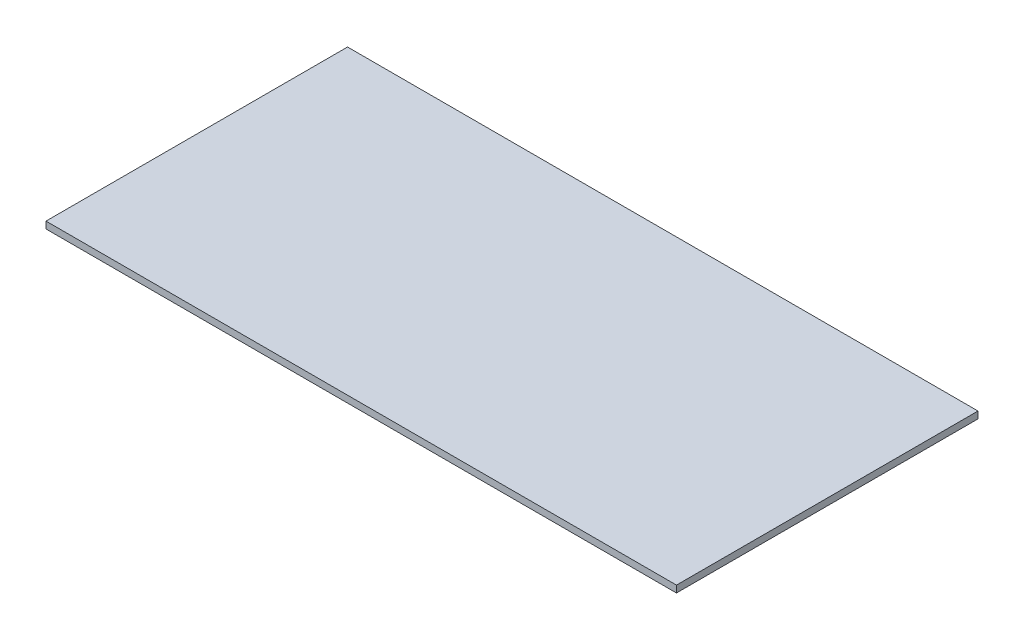
SolidWorks part; units mm, degrees
material "Acrylic (Medium-high impact)"
ref_plane "Front Plane" through (0, 0, 0) normal (0, 0, 1) x (1, 0, 0)
ref_plane "Top Plane" through (0, 0, 0) normal (0, 1, 0) x (1, 0, 0)
ref_plane "Right Plane" through (0, 0, 0) normal (1, 0, 0) x (0, 0, -1)
sketch "Sketch1" plane through (0, 0, 0) normal (0, 1, 0) x (1, 0, 0)
  line L1 (-292.1, 139.7) -> (292.1, 139.7)
  line L2 (-292.1, 139.7) -> (-292.1, -139.7)
  line L3 (-292.1, -139.7) -> (292.1, -139.7)
  line L4 (292.1, 139.7) -> (292.1, -139.7)
  line L5 (-292.1, 139.7) -> (292.1, -139.7) construction
  line L6 (-292.1, -139.7) -> (292.1, 139.7) construction
  point P4 (0, 0)
  dimension "D1" = 279.4
  dimension "D2" = 584.2
extrude "Baseplate" add sketch "Sketch1" along normal blind 6.35
sketch "Mounting Points" plane through (0, 6.35, 0) normal (0, 1, 0) x (1, 0, 0)
  line L0 (-292.1, -127) -> (292.1, -127) construction
  line L1 (-292.1, 139.7) -> (-292.1, -139.7) construction
  line L2 (292.1, -139.7) -> (292.1, 139.7) construction
  line L3 (-292.1, -139.7) -> (292.1, -139.7) construction
  line L4 (-55, 0) -> (55, 0) construction
  line L5 (-292.1, 127) -> (292.1, 127) construction
  point P8 (133.35, -127)
  point P9 (-240.5126, -127)
  point P10 (-19.05, -127)
  point P11 (-69.85, -127)
  point P20 (-69.85, 127)
  point P21 (-19.05, 127)
  point P22 (-240.5126, 127)
  point P23 (133.35, 127)
  dimension "D1" = 12.7
  dimension "D2" = 158.75
  dimension "D3" = 50.8
  dimension "D4" = 152.4
  dimension "D5" = 170.6626
sketch "Battery Adaptors" plane through (0, 6.35, 0) normal (0, 1, 0) x (1, 0, 0)
  line L0 (208.4146, -118.6932) -> (290.6217, -118.6932) construction
  line L1 (208.4146, -118.6932) -> (208.4146, -20.2682) construction
  line L2 (208.4146, -20.2682) -> (290.6217, -20.2682) construction
  line L3 (290.6217, -118.6932) -> (290.6217, -20.2682) construction
  line L8 (121.1275, -118.6932) -> (203.3346, -118.6932) construction
  line L9 (121.1275, -118.6932) -> (121.1275, -20.2682) construction
  line L10 (121.1275, -20.2682) -> (203.3346, -20.2682) construction
  line L11 (203.3346, -118.6932) -> (203.3346, -20.2682) construction
  point P0 (215.3646, -25.6682)
  point P5 (283.6717, -25.6682)
  point P6 (269.3117, -113.2932)
  point P7 (229.7246, -113.2932)
  point P14 (128.0775, -25.6682)
  point P19 (196.3846, -25.6682)
  point P20 (182.0246, -113.2932)
  point P21 (142.4375, -113.2932)
  dimension "D1" = 98.425
  dimension "D2" = 82.2071
  dimension "D3" = 5.4
  dimension "D4" = 5.4
  dimension "D5" = 6.95
  dimension "D6" = 6.95
  dimension "D7" = 21.31
  dimension "D8" = 21.31
  dimension "D11" = 98.425
  dimension "D12" = 82.2071
  dimension "D13" = 6.95
  dimension "D14" = 6.95
  dimension "D15" = 21.31
  dimension "D16" = 21.31
  dimension "D17" = 5.08
sketch "Orin Nano" plane through (0, 6.35, 0) normal (0, 1, 0) x (1, 0, 0)
  line L1 (90.5015, 112.6346) -> (193.3715, 112.6346) construction
  line L2 (90.5015, 112.6346) -> (90.5015, -1.6654) construction
  line L3 (90.5015, -1.6654) -> (193.3715, -1.6654) construction
  line L4 (193.3715, 112.6346) -> (193.3715, -1.6654) construction
  point P4 (94.3115, 108.8246)
  point P5 (189.5615, 108.8246)
  point P6 (189.5615, 2.1446)
  point P7 (94.3115, 2.1446)
  dimension "D1" = 114.3
  dimension "D2" = 102.87
  dimension "D3" = 3.81
  dimension "D4" = 3.81
  dimension "D5" = 3.81
  dimension "D6" = 3.81
sketch "Air Tank Shadow" plane through (0, 6.35, 0) normal (0, 1, 0) x (1, 0, 0)
  line L1 (-342.6787, 115.7653) -> (-182.6587, 115.7653) construction
  line L2 (-342.6787, 115.7653) -> (-342.6787, -23.9347) construction
  line L3 (-342.6787, -23.9347) -> (-182.6587, -23.9347) construction
  line L4 (-182.6587, 115.7653) -> (-182.6587, -23.9347) construction
  line L5 (-342.6787, 115.7653) -> (-182.6587, -23.9347) construction
  line L6 (-342.6787, -23.9347) -> (-182.6587, 115.7653) construction
  point P4 (-262.6687, 45.9153)
  dimension "D1" = 160.02
  dimension "D2" = 139.7
sketch "Router Shadow" plane through (0, 6.35, 0) normal (0, 1, 0) x (1, 0, 0)
  line L1 (-192.9184, 98.6941) -> (-65.9184, 98.6941) construction
  line L2 (-192.9184, 98.6941) -> (-192.9184, -104.5059) construction
  line L3 (-192.9184, -104.5059) -> (-65.9184, -104.5059) construction
  line L4 (-65.9184, 98.6941) -> (-65.9184, -104.5059) construction
  line L5 (-192.9184, 98.6941) -> (-65.9184, -104.5059) construction
  line L6 (-192.9184, -104.5059) -> (-65.9184, 98.6941) construction
  point P4 (-129.4184, -2.9059)
  dimension "D1" = 203.2
  dimension "D2" = 127
sketch "PCB Mount" plane through (0, 6.35, 0) normal (0, 1, 0) x (1, 0, 0)
  line L1 (-60.8861, 132.0384) -> (85.1639, 132.0384) construction
  line L2 (-60.8861, 132.0384) -> (-60.8861, -14.0116) construction
  line L3 (-60.8861, -14.0116) -> (85.1639, -14.0116) construction
  line L4 (85.1639, 132.0384) -> (85.1639, -14.0116) construction
  line L5 (-60.8861, 132.0384) -> (85.1639, -14.0116) construction
  line L6 (-60.8861, -14.0116) -> (85.1639, 132.0384) construction
  point P4 (12.1389, 59.0134)
  dimension "D1" = 146.05
  dimension "D2" = 146.05
sketch "Power Distribution" plane through (0, 6.35, 0) normal (0, 1, 0) x (1, 0, 0)
  line L1 (105.2134, -158.0614) -> (232.2134, -158.0614) construction
  line L2 (105.2134, -158.0614) -> (105.2134, -196.1614) construction
  line L3 (105.2134, -196.1614) -> (232.2134, -196.1614) construction
  line L4 (232.2134, -158.0614) -> (232.2134, -196.1614) construction
  line L5 (105.2134, -158.0614) -> (232.2134, -196.1614) construction
  line L6 (105.2134, -196.1614) -> (232.2134, -158.0614) construction
  point P4 (168.7134, -177.1114)
  dimension "D1" = 38.1
  dimension "D2" = 127
sketch "Voltage Regulators" plane through (0, 6.35, 0) normal (0, 1, 0) x (1, 0, 0)
  line L1 (-52.1195, -25.3804) -> (81.2305, -25.3804) construction
  line L2 (-52.1195, -25.3804) -> (-52.1195, -126.9804) construction
  line L3 (-52.1195, -126.9804) -> (81.2305, -126.9804) construction
  line L4 (81.2305, -25.3804) -> (81.2305, -126.9804) construction
  line L5 (-52.1195, -25.3804) -> (81.2305, -126.9804) construction
  line L6 (-52.1195, -126.9804) -> (81.2305, -25.3804) construction
  point P4 (14.5555, -76.1804)
  dimension "D1" = 133.35
  dimension "D2" = 101.6
sketch "Stepper Driver" plane through (0, 6.35, 0) normal (0, 1, 0) x (1, 0, 0)
  line L1 (198.5846, 111.6277) -> (287.4846, 111.6277) construction
  line L2 (198.5846, 111.6277) -> (198.5846, -2.6723) construction
  line L3 (198.5846, -2.6723) -> (287.4846, -2.6723) construction
  line L4 (287.4846, 111.6277) -> (287.4846, -2.6723) construction
  line L5 (198.5846, 111.6277) -> (287.4846, -2.6723) construction
  line L6 (198.5846, -2.6723) -> (287.4846, 111.6277) construction
  point P4 (243.0346, 54.4777)
  dimension "D1" = 88.9
  dimension "D2" = 114.3
